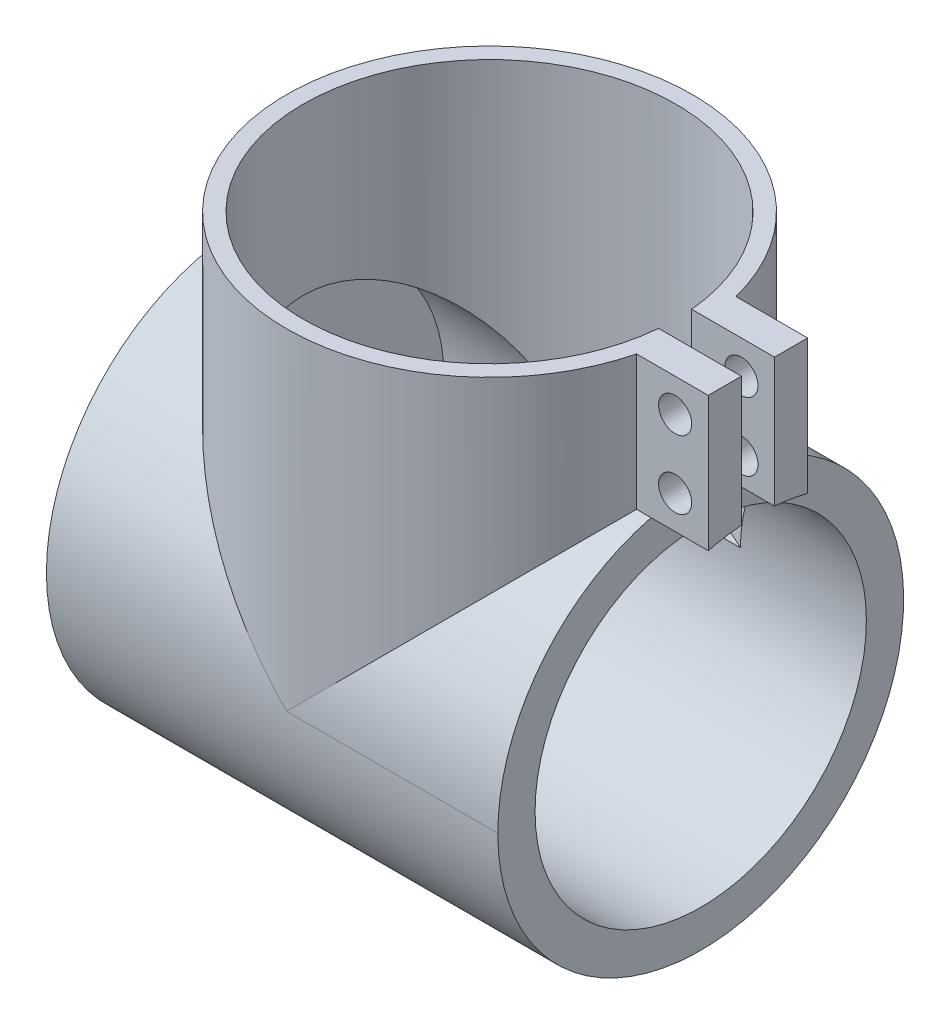
SolidWorks part; units mm, degrees
ref_plane "Спереди" through (0, 0, 0) normal (0, 0, 1) x (1, 0, 0)
ref_plane "Сверху" through (0, 0, 0) normal (0, 1, 0) x (1, 0, 0)
ref_plane "Справа" through (0, 0, 0) normal (1, 0, 0) x (0, 0, -1)
sketch "Эскиз1" plane through (0, 0, 0) normal (1, 0, 0) x (0, 0, -1)
  circle A0 centre (0, 0) radius 24.5
  dimension "D1" = 49
extrude "Бобышка-Вытянуть1" add sketch "Эскиз1" along normal blind 55
sketch "Эскиз2" plane through (0, 0, 0) normal (0, 1, 0) x (1, 0, 0)
  circle A0 centre (29.5, 0) radius 24.5
  dimension "D1" = 49
  dimension "D2" = 29.5
extrude "Бобышка-Вытянуть2" add sketch "Эскиз2" along normal blind 40
sketch "Эскиз3" plane through (55, 0, 0) normal (1, 0, 0) x (0, 0, -1)
  circle A0 centre (0, 0) radius 20
  dimension "D1" = 40
extrude "Вырез-Вытянуть1" cut sketch "Эскиз3" against normal blind 51
sketch "Эскиз4" plane through (0, 0, 0) normal (-1, 0, 0) x (0, 0, 1)
  circle A0 centre (7, 0) radius 1.5
  dimension "D2" = 3
  dimension "D1" = 7
extrude "Вырез-Вытянуть2" cut sketch "Эскиз4" against normal through all
pattern_circular "Круговой массив1" count 4 over 360 about axis through (0, 0, 0) along (1, 0, 0) of "Вырез-Вытянуть2"
sketch "Эскиз5" plane through (0, 40, 0) normal (0, 1, 0) x (1, 0, 0)
  circle A0 centre (29.5, 0) radius 22.5
  dimension "D2" = 45
  dimension "D1" = 29.5
extrude "Вырез-Вытянуть3" cut sketch "Эскиз5" against normal blind 40
sketch "Эскиз6" plane through (0, 40, 0) normal (0, 1, 0) x (1, 0, 0)
  line L0 (0, 0) -> (64.6792, 0) construction
  line L1 (0, 24.5) -> (0, -24.5) construction
  line L3 (48, 2) -> (56, 2)
  line L4 (48, 2) -> (48, -2)
  line L5 (48, -2) -> (56, -2)
  line L6 (56, 2) -> (56, -2)
  dimension "D1" = 48
  dimension "D2" = 4
  dimension "D3" = 2
  dimension "D4" = 8
extrude "Вырез-Вытянуть5" cut sketch "Эскиз6" against normal up to surface (15.5818 mm away)
sketch "Эскиз7" plane through (0, 40, 0) normal (0, 1, 0) x (1, 0, 0)
  line L0 (51.9109, -2) -> (61.9109, -2)
  line L1 (61.9109, -2) -> (61.9109, -6)
  line L2 (61.9109, -6) -> (51.1852, -6)
  line L3 (51.9109, 2) -> (61.9109, 2)
  line L4 (61.9109, 2) -> (61.9109, 6)
  line L5 (61.9109, 6) -> (51.1852, 6)
  arc A0 (51.1852, -6) -> (51.9109, -2) centre (29.5, 0) ccw
  arc A1 (51.9109, 2) -> (51.1852, 6) centre (29.5, 0) ccw
  dimension "D1" = 45
  dimension "D2" = 10
  dimension "D3" = 4
  dimension "D4" = 10
  dimension "D5" = 4
extrude "Бобышка-Вытянуть3" add sketch "Эскиз7" against normal up to surface (16.2461 mm away)
sketch "Эскиз8" plane through (0, 0, -6) normal (0, 0, -1) x (-1, 0, 0)
  line L0 (-61.9109, 23.7539) -> (-61.9109, 40) construction
  line L1 (-61.9109, 40) -> (-53.2539, 40) construction
  line L2 (-61.9109, 23.7539) -> (-55, 23.7539) construction
  circle A0 centre (-57.9109, 36) radius 2
  circle A1 centre (-57.9109, 27.7539) radius 2
  dimension "D5" = 4
  dimension "D6" = 4
  dimension "D1" = 4
  dimension "D2" = 4
  dimension "D3" = 4
  dimension "D4" = 4
extrude "Вырез-Вытянуть6" cut sketch "Эскиз8" against normal through all
sketch "Эскиз9" plane through (0, 0, 0) normal (-1, 0, 0) x (0, 0, 1)
  circle A0 centre (0, 0) radius 15
  circle A1 centre (0, 0) radius 24.5
  dimension "D1" = 30
  dimension "D2" = 49
extrude "Вырез-Вытянуть7" cut sketch "Эскиз9" against normal blind 0.5
